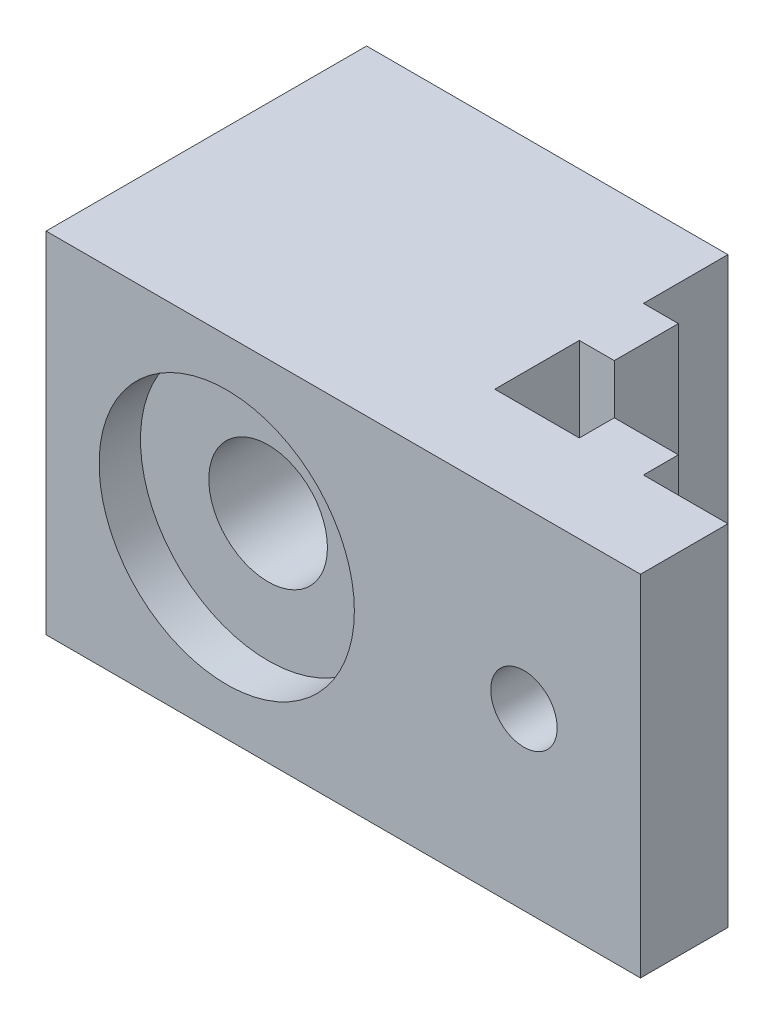
SolidWorks part; units mm, degrees
ref_plane "Спереди" through (0, 0, 0) normal (0, 0, 1) x (1, 0, 0)
ref_plane "Сверху" through (0, 0, 0) normal (0, 1, 0) x (1, 0, 0)
ref_plane "Справа" through (0, 0, 0) normal (1, 0, 0) x (0, 0, -1)
sketch "Эскиз1" plane through (0, 0, 0) normal (0, 0, 1) x (1, 0, 0)
  line L1 (-25.5, -15) -> (25.5, -15)
  line L2 (-25.5, -15) -> (-25.5, 15)
  line L3 (-25.5, 15) -> (25.5, 15)
  line L4 (25.5, -15) -> (25.5, 15)
  line L5 (-25.5, -15) -> (25.5, 15) construction
  line L6 (-25.5, 15) -> (25.5, -15) construction
  point P0 (0, 0)
  dimension "D1" = 51
  dimension "D2" = 30
extrude "Бобышка-Вытянуть5" add sketch "Эскиз1" along normal blind 7.5
sketch "Эскиз4" plane through (0, 0, 0) normal (0, 0, -1) x (-1, 0, 0)
  line L0 (-5.5, -15) -> (-5.5, 15)
  line L1 (25.5, -15) -> (-25.5, -15) construction
  line L2 (-25.5, 15) -> (25.5, 15) construction
  line L3 (-5.5, 15) -> (-5.5, -15)
  line L4 (-25.5, -15) -> (-25.5, 15) construction
  line M3 (-25.5, -15) -> (25.5, -15)
  line M4 (25.5, -15) -> (25.5, 15)
  line M5 (25.5, 15) -> (-25.5, 15)
  dimension "D1" = 20
extrude "Бобышка-Вытянуть6" add sketch "Эскиз4" along normal blind 20 contours L0 M3 M4 M5
sketch "Эскиз5" plane through (0, 0, 0) normal (0, 0, -1) x (-1, 0, 0)
  line L0 (-18.25, 15) -> (-18.25, -15)
  line L1 (-25.5, 15) -> (-5.5, 15) construction
  line L2 (-5.5, -15) -> (-25.5, -15) construction
  line L3 (-18.25, -15) -> (-18.25, 15)
  line L4 (-12.75, 15) -> (-12.75, -15)
  line L5 (-25.5, -15) -> (-25.5, 15) construction
  line L6 (-5.5, -15) -> (-5.5, 15) construction
  dimension "D1" = 7.25
  dimension "D2" = 7.25
sketch "Эскиз6" plane through (0, 0, 0) normal (0, 0, -1) x (-1, 0, 0)
  line L0 (-18.25, 15) -> (-18.25, -15)
  line L1 (-18.25, -15) -> (-12.75, -15)
  line L2 (-12.75, -15) -> (-12.75, 15)
  line L3 (-12.75, 15) -> (-18.25, 15)
  line L4 (-18.25, 5) -> (-12.75, 5)
  line L5 (-18.25, -5) -> (-12.75, -5)
  line M1 (-25.5, -15) -> (-5.5, -15)
  line M3 (-5.5, 15) -> (-25.5, 15)
  dimension "D1" = 10
  dimension "D2" = 10
extrude "Бобышка-Вытянуть9" add sketch "Эскиз6" along normal blind 3 contours L0 L4 L2 M3 | L5 L0 L2 M1
sketch "Эскиз10" plane through (5.5, 0, 0) normal (1, 0, 0) x (0, 0, -1)
  line L0 (7.25, 15) -> (7.25, -15)
  line L1 (20, 15) -> (0, 15) construction
  line L2 (20, -15) -> (0, -15) construction
  line L3 (12.75, 15) -> (12.75, -15)
  line L4 (0, -15) -> (0, 15) construction
  line L5 (20, -15) -> (20, 15) construction
  line L6 (7.25, 5) -> (12.75, 5)
  line L7 (7.25, -5) -> (12.75, -5)
  line L8 (7.25, 15) -> (7.25, 5)
  line L9 (7.25, 15) -> (12.75, 15)
  line L10 (7.25, 5) -> (12.75, 5)
  line L11 (12.75, 15) -> (12.75, 5)
  line M6 (0, -15) -> (20, -15)
  line M8 (20, 15) -> (0, 15)
  dimension "D1" = 7.25
  dimension "D2" = 7.25
  dimension "D3" = 10
  dimension "D4" = 10
extrude "Бобышка-Вытянуть10" add sketch "Эскиз10" along normal blind 3 contours L0 L6 L3 M8 | L7 L0 L3 M6
sketch "Эскиз11" plane through (0, 0, 7.5) normal (0, 0, 1) x (1, 0, 0)
  line L0 (5.5, 15) -> (5.5, -15)
  line L1 (25.5, 15) -> (-25.5, 15) construction
  line L2 (-25.5, -15) -> (25.5, -15) construction
  line L3 (25.5, -15) -> (25.5, 15) construction
  line L4 (-10, 15) -> (-10, -15)
  circle A0 centre (-10, 0) radius 10.95
  point P10 (-10, 0)
  dimension "D1" = 20
  dimension "D2" = 15.5
sketch "Эскиз13" plane through (0, 0, 7.5) normal (0, 0, 1) x (1, 0, 0)
  circle A0 centre (-10, 0) radius 10.95
  dimension "D1" = 21.9
extrude "Вырез-Вытянуть1" cut sketch "Эскиз13" against normal blind 3.55
sketch "Эскиз14" plane through (0, 0, 3.95) normal (0, 0, 1) x (1, 0, 0)
  line L0 (-10, 15) -> (-10, -15)
  circle A0 centre (-10, 0) radius 5.09
  point P4 (-10, 0)
extrude "Вырез-Вытянуть2" cut sketch "Эскиз14" against normal blind 10.3 contours L0 A0 | L0 A0
sketch "Эскиз15" plane through (0, 0, -6.35) normal (0, 0, 1) x (1, 0, 0)
  line L0 (-10, 15) -> (-10, -15)
  circle A0 centre (-10, 0) radius 4.3
  point P4 (-10, 0)
extrude "Вырез-Вытянуть3" cut sketch "Эскиз15" against normal through all contours L0 A0 | L0 A0
sketch "Эскиз16" plane through (0, 0, 7.5) normal (0, 0, 1) x (1, 0, 0)
  line L0 (15.5, 15) -> (15.5, -15)
  line L2 (12.75, -15) -> (18.25, -15)
  line L3 (25.5, 15) -> (-25.5, 15) construction
  circle A0 centre (15.5, 0) radius 2.8
  point P10 (15.5, 0)
extrude "Вырез-Вытянуть5" cut sketch "Эскиз16" against normal through all contours L0 A0 | L0 A0
sketch "Эскиз17" plane through (-25.5, 0, 0) normal (-1, 0, 0) x (0, 0, 1)
  line L0 (7.5, 0) -> (-20, 0)
  line L1 (7.5, 15) -> (7.5, -15) construction
  line L2 (-20, -15) -> (-20, 15) construction
  circle A0 centre (-10, 0) radius 2.6
  point P6 (-10, 0)
  dimension "D1" = 10
extrude "Вырез-Вытянуть7" cut sketch "Эскиз17" against normal through all contours L0 A0 | L0 A0
sketch "Эскиз18" plane through (0, 0, 3.95) normal (0, 0, 1) x (1, 0, 0)
sketch "Эскиз20" plane through (0, 0, 3.95) normal (0, 0, 1) x (1, 0, 0)
  circle A0 centre (-10.6268, 0) radius 8.02
  circle A1 centre (-18.6468, 0) radius 1.0587
  point P3 (-18.6468, 0)
sketch "Эскиз21" plane through (0, 15, 0) normal (0, 1, 0) x (1, 0, 0)
  line L0 (25.5, 0) -> (5.5, 0)
  dimension "D1" = 7.25
  dimension "D2" = 7.25
sketch "Эскиз22" plane through (0, 0, 0) normal (0, 0, -1) x (-1, 0, 0)
  line L0 (-18.25, -15) -> (-12.75, -15)
  line L1 (-15.5, -15) -> (-15.5, 15)
  line L2 (-25.5, 15) -> (-5.5, 15) construction
  circle A1 centre (-15.5, 0) radius 2.85
  circle A2 centre (-15.5, 0) radius 2.8
  point P10 (-15.5, 0)
  dimension "D1" = 5.7
sketch "Эскиз23" plane through (-25.5, 0, 0) normal (-1, 0, 0) x (0, 0, 1)
  line L0 (-20, 0) -> (7.5, 0)
  line L1 (-20, -15) -> (-20, 15) construction
  line L2 (7.5, 15) -> (7.5, -15) construction
  circle A0 centre (-10, 0) radius 2.85
  point P6 (-10, 0)
  circle M1 centre (-10, 0) radius 2.6
extrude "Бобышка-Вытянуть12" add sketch "Эскиз23" against normal blind 31 contours L0 M1 | L0 M1
sketch "Эскиз24" plane through (-25.5, 0, 0) normal (-1, 0, 0) x (0, 0, 1)
  line L0 (-20, 0) -> (7.5, 0)
  line L1 (-20, -15) -> (-20, 15) construction
  line L2 (7.5, 15) -> (7.5, -15) construction
  circle A0 centre (-10, 0) radius 2.85
  point P6 (-10, 0)
  dimension "D1" = 10
extrude "Вырез-Вытянуть13" cut sketch "Эскиз24" against normal through all contours L0 A0 | L0 A0
sketch "Эскиз27" plane through (0, 0, 7.5) normal (0, 0, 1) x (1, 0, 0)
  line L0 (25.5, -15) -> (15.5, -15)
  line L1 (15.5, -15) -> (15.5, 15)
  line L2 (25.5, 15) -> (-25.5, 15) construction
  circle A0 centre (15.5, 0) radius 2.8
  point P4 (15.5, 0)
  circle M1 centre (15.5, 0) radius 2.8
  dimension "D1" = 10
extrude "Бобышка-Вытянуть14" add sketch "Эскиз27" against normal blind 7.5 contours L1 M1 | L1 M1
sketch "Эскиз28" plane through (0, 0, 7.5) normal (0, 0, 1) x (1, 0, 0)
  line L0 (25.5, -15) -> (15.5, -15)
  line L1 (-25.5, -15) -> (25.5, -15) construction
  line L2 (15.5, -15) -> (15.5, 15)
  line L3 (25.5, 15) -> (-25.5, 15) construction
  circle A0 centre (15.5, 0) radius 2.85
  point P5 (15.5, 0)
  dimension "D1" = 10
extrude "Вырез-Вытянуть14" cut sketch "Эскиз28" against normal through all contours L2 A0 | L2 A0
sketch "Эскиз29" plane through (0, -15, 0) normal (0, -1, 0) x (1, 0, 0)
  line L0 (-25.5, 7.5) -> (25.5, 7.5) construction
  line L1 (5.5, -12.85) -> (5.5, -7.15) construction
  point P0 (5.5, -7.25)
  point P1 (5.5, -12.75)
  point P3 (5.5, -20)
  point P6 (5.5, 7.5)
  point P9 (8.5, -7.25)
  dimension "D1" = 5.5
  dimension "D2" = 20
  dimension "D3" = 7.5
  dimension "D4" = 7.25
  dimension "D5" = 3
sketch "Эскиз30" plane through (5.5, 0, 0) normal (1, 0, 0) x (0, 0, -1)
  line L0 (0, -2.85) -> (0, 2.85) construction
  line L1 (7.25, -15) -> (0, -15) construction
  point P0 (12.75, -5)
  point P1 (12.75, 5)
